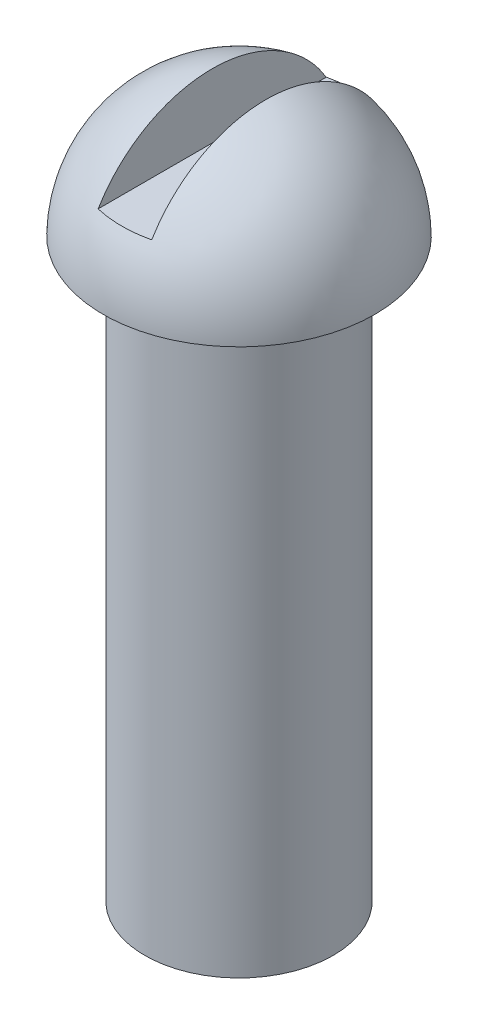
SolidWorks part; units mm, degrees
ref_plane "Front" through (0, 0, 0) normal (0, 0, 1) x (1, 0, 0)
ref_plane "Top" through (0, 0, 0) normal (0, 1, 0) x (1, 0, 0)
ref_plane "Right" through (0, 0, 0) normal (1, 0, 0) x (0, 0, -1)
sketch "Sketch1" plane through (0, 0, 0) normal (0, 0, 1) x (1, 0, 0)
  line L0 (0, 10.1105) -> (0, -21.844) construction
  line L1 (5.1562, 0) -> (3.5719, 0)
  line L2 (3.5719, 0) -> (3.5719, -21.844)
  line L3 (3.5719, -21.844) -> (0, -21.844)
  line L4 (0, -21.844) -> (0, 5.08)
  line L5 (0, 5.08) -> (-4.8734, 5.08) construction
  line L6 (50, 0) -> (-50, 0) construction
  arc A0 (0, 5.08) -> (5.1562, 0) centre (0, -0.0768) cw
  dimension "D1" = 10.3124
  dimension "D2" = 7.1437
  dimension "D3" = 26.924
  dimension "D4" = 5.08
revolve "Base-Revolve" add sketch "Sketch1" angle 360 about L0
sketch "Sketch2" plane through (0, 0, 0) normal (0, 0, 1) x (1, 0, 0)
  line L1 (-1.016, 4.9789) -> (-1.016, 2.54)
  line L2 (1.016, 2.54) -> (-1.016, 2.54)
  line L3 (1.016, 2.54) -> (1.016, 4.9789)
  line L5 (0, 2.9275) -> (0, -3.9159) construction
  line L6 (0, -21.844) -> (0, 0) construction
  arc A4 (1.016, 4.9789) -> (-1.016, 4.9789) centre (0, -0.0768) ccw
  dimension "D1" = 2.032
  dimension "D2" = 2.54
extrude "Cut-Extrude1" cut sketch "Sketch2" against normal through all and the other way through all
